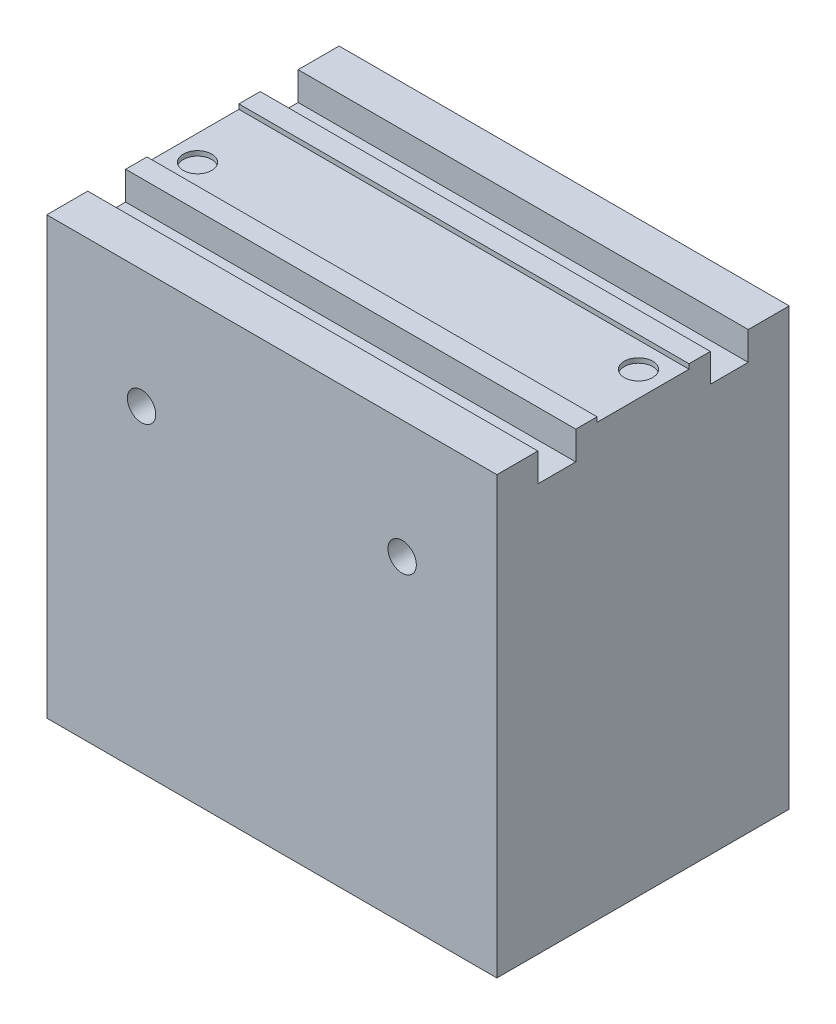
SolidWorks part; units mm, degrees
ref_plane "前视基准面" through (0, 0, 0) normal (0, 0, 1) x (1, 0, 0)
ref_plane "上视基准面" through (0, 0, 0) normal (0, 1, 0) x (1, 0, 0)
ref_plane "右视基准面" through (0, 0, 0) normal (1, 0, 0) x (0, 0, -1)
sketch "草图1" plane through (0, 0, 0) normal (0, 1, 0) x (1, 0, 0)
  line L1 (-47.5, -30.85) -> (47.5, -30.85)
  line L2 (-47.5, -30.85) -> (-47.5, 30.85)
  line L3 (-47.5, 30.85) -> (47.5, 30.85)
  line L4 (47.5, -30.85) -> (47.5, 30.85)
  line L5 (-47.5, -30.85) -> (47.5, 30.85) construction
  line L6 (-47.5, 30.85) -> (47.5, -30.85) construction
  point P0 (0, 0)
  dimension "D1" = 95
  dimension "D2" = 61.7
extrude "凸台-拉伸1" add sketch "草图1" along normal blind 93
sketch "草图3" plane through (0, 93, 0) normal (0, 1, 0) x (1, 0, 0)
  line L0 (47.5, -30.85) -> (47.5, 30.85) construction
  line L1 (-47.5, -9.7) -> (47.5, -9.7)
  line L2 (-47.5, -9.7) -> (-47.5, 9.7)
  line L3 (-47.5, 9.7) -> (47.5, 9.7)
  line L4 (47.5, -9.7) -> (47.5, 9.7)
  line L5 (-47.5, -9.7) -> (47.5, 9.7) construction
  line L6 (-47.5, 9.7) -> (47.5, -9.7) construction
  point P0 (0, 0)
  dimension "D1" = 9.7
extrude "切除-拉伸1" cut sketch "草图3" against normal blind 1 flip side to cut
sketch "草图4" plane through (0, 93, 0) normal (0, 1, 0) x (1, 0, 0)
  line L0 (-42.1961, -4.3382) -> (42.1961, 4.3382) construction
  circle A0 centre (-42.1961, -4.3382) radius 3
  circle A1 centre (42.1961, 4.3382) radius 3
  point P6 (0, 0)
  dimension "D1" = 6
  dimension "D2" = 2
extrude "切除-拉伸2" cut sketch "草图4" against normal blind 3
sketch "草图5" plane through (0, 92, 0) normal (0, 1, 0) x (1, 0, 0)
  line L0 (-1000, 0) -> (49000, 0) construction
  line L1 (-47.5, -9.7) -> (-47.5, -30.85) construction
  line L2 (-47.5, -22.2) -> (47.5, -22.2)
  line L3 (-47.5, -22.2) -> (-47.5, -14.2)
  line L4 (-47.5, -14.2) -> (47.5, -14.2)
  line L5 (47.5, -22.2) -> (47.5, -14.2)
  line L6 (47.5, -30.85) -> (47.5, -9.7) construction
  line L7 (-47.5, -9.7) -> (47.5, -9.7) construction
  line L8 (-47.5, 14.2) -> (47.5, 14.2)
  line L9 (47.5, 22.2) -> (47.5, 14.2)
  line L10 (-47.5, 22.2) -> (47.5, 22.2)
  line L11 (-47.5, 22.2) -> (-47.5, 14.2)
  point P11 (47.5, -18.2)
  dimension "D1" = 8.5
  dimension "D2" = 8
extrude "切除-拉伸3" cut sketch "草图5" against normal blind 6
sketch "草图6" plane through (0, 93, 0) normal (0, 1, 0) x (1, 0, 0)
  line L4 (-47.5, -9.7) -> (47.5, -9.7)
  line L5 (47.5, -9.7) -> (47.5, 9.7)
  line L6 (47.5, 9.7) -> (-47.5, 9.7)
  line L7 (-47.5, 9.7) -> (-47.5, -9.7)
  line L8 (-47.5, -9.7) -> (47.5, -9.7)
  line L9 (47.5, -9.7) -> (47.5, 9.7)
  line L10 (47.5, 9.7) -> (-47.5, 9.7)
  line L11 (-47.5, 9.7) -> (-47.5, -9.7)
  dimension "D1" = 0
extrude "切除-拉伸4" cut sketch "草图6" against normal blind 2
sketch "草图7" plane through (0, 0, 30.85) normal (0, 0, 1) x (1, 0, 0)
  line L0 (-47.5, 92) -> (47.5, 92) construction
  line L1 (0, -1000) -> (0, 49000) construction
  circle A0 centre (-27.5, 67) radius 3
  circle A1 centre (27.5, 67) radius 3
  dimension "D1" = 6
  dimension "D2" = 27.5
  dimension "D3" = 25
extrude "切除-拉伸5" cut sketch "草图7" against normal through all
